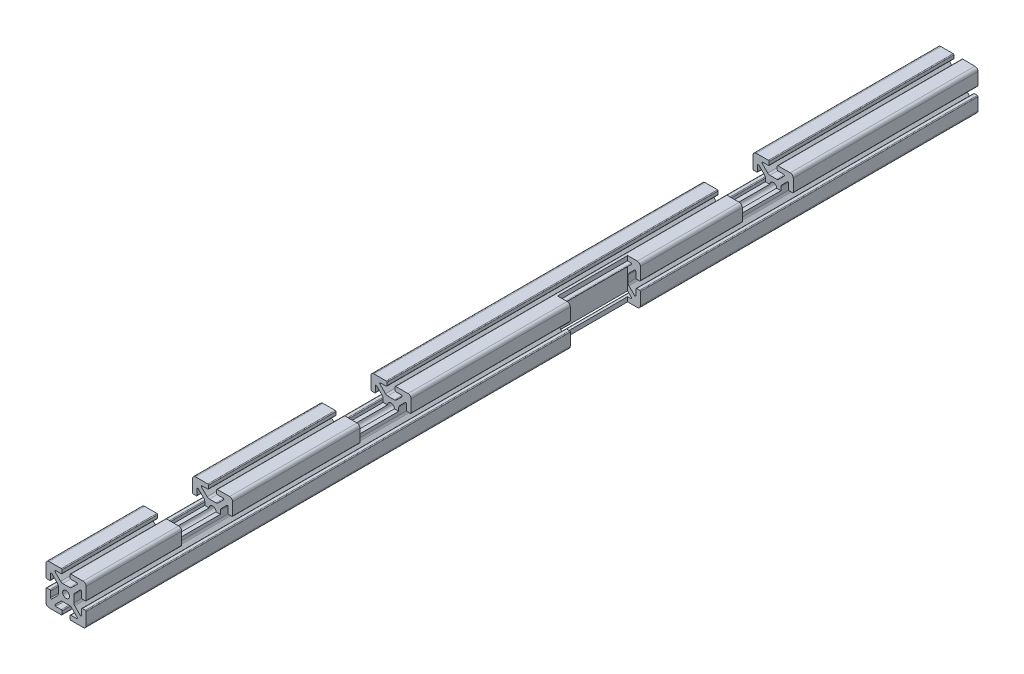
SolidWorks part; units mm, degrees
ref_plane "Front Plane" through (0, 0, 0) normal (0, 0, 1) x (1, 0, 0)
ref_plane "Top Plane" through (0, 0, 0) normal (0, 1, 0) x (1, 0, 0)
ref_plane "Right Plane" through (0, 0, 0) normal (1, 0, 0) x (0, 0, -1)
sketch "Sketch1" plane through (0, 0, 0) normal (0, 0, 1) x (1, 0, 0)
  line L0 (0, 20) -> (0, -20) construction
  line L1 (-20, 0) -> (20, 0) construction
  line L2 (-20, 16.952) -> (-20, 4.7625)
  line L3 (-16.952, 20) -> (-4.7625, 20)
  line L4 (-4.0005, 19.238) -> (-4.0005, 16.2662)
  line L5 (-4.7625, 15.5042) -> (-10.4856, 15.5042)
  line L6 (-11.0244, 14.2034) -> (-5.456, 8.6351)
  line L7 (-14.2034, 11.0244) -> (-8.6351, 5.456)
  line L8 (-15.5042, 10.4856) -> (-15.5042, 4.7625)
  line L9 (-16.2662, 4.0005) -> (-19.238, 4.0005)
  line L10 (0, 0) -> (-20, 20) construction
  line L11 (-3.3367, 7.7572) -> (3.3367, 7.7572)
  line L12 (-7.7572, 3.3367) -> (-7.7572, -3.3367)
  line L13 (16.2662, 4.0005) -> (19.238, 4.0005)
  line L14 (15.5042, 10.4856) -> (15.5042, 4.7625)
  line L15 (20, 16.952) -> (20, 4.7625)
  line L16 (16.952, 20) -> (4.7625, 20)
  line L17 (4.0005, 19.238) -> (4.0005, 16.2662)
  line L18 (4.7625, 15.5042) -> (10.4856, 15.5042)
  line L19 (7.7572, 3.3367) -> (7.7572, -3.3367)
  line L20 (11.0244, 14.2034) -> (5.456, 8.6351)
  line L21 (14.2034, 11.0244) -> (8.6351, 5.456)
  line L22 (-16.2662, -4.0005) -> (-19.238, -4.0005)
  line L23 (-15.5042, -10.4856) -> (-15.5042, -4.7625)
  line L24 (-14.2034, -11.0244) -> (-8.6351, -5.456)
  line L25 (-11.0244, -14.2034) -> (-5.456, -8.6351)
  line L26 (-4.7625, -15.5042) -> (-10.4856, -15.5042)
  line L27 (-4.0005, -19.238) -> (-4.0005, -16.2662)
  line L28 (-16.952, -20) -> (-4.7625, -20)
  line L29 (-20, -16.952) -> (-20, -4.7625)
  line L30 (20, -16.952) -> (20, -4.7625)
  line L31 (16.952, -20) -> (4.7625, -20)
  line L32 (4.0005, -19.238) -> (4.0005, -16.2662)
  line L33 (4.7625, -15.5042) -> (10.4856, -15.5042)
  line L34 (11.0244, -14.2034) -> (5.456, -8.6351)
  line L35 (14.2034, -11.0244) -> (8.6351, -5.456)
  line L36 (15.5042, -10.4856) -> (15.5042, -4.7625)
  line L37 (16.2662, -4.0005) -> (19.238, -4.0005)
  line L38 (-3.3367, -7.7572) -> (3.3367, -7.7572)
  circle A0 centre (0, 0) radius 3.4036
  arc A1 (-20, 16.952) -> (-16.952, 20) centre (-16.952, 16.952) cw
  arc A2 (-14.2034, 11.0244) -> (-15.5042, 10.4856) centre (-14.7422, 10.4856) ccw
  arc A3 (-10.4856, 15.5042) -> (-11.0244, 14.2034) centre (-10.4856, 14.7422) ccw
  arc A4 (-4.7625, 20) -> (-4.0005, 19.238) centre (-4.7625, 19.238) cw
  arc A5 (-20, 4.7625) -> (-19.238, 4.0005) centre (-19.238, 4.7625) ccw
  arc A6 (-15.5042, 4.7625) -> (-16.2662, 4.0005) centre (-16.2662, 4.7625) cw
  arc A7 (-4.0005, 16.2662) -> (-4.7625, 15.5042) centre (-4.7625, 16.2662) cw
  arc A8 (-3.3367, 7.7572) -> (-5.456, 8.6351) centre (-3.3367, 10.7544) cw
  arc A9 (-7.7572, 3.3367) -> (-8.6351, 5.456) centre (-10.7544, 3.3367) ccw
  arc A10 (15.5042, 4.7625) -> (16.2662, 4.0005) centre (16.2662, 4.7625) ccw
  arc A11 (20, 4.7625) -> (19.238, 4.0005) centre (19.238, 4.7625) cw
  arc A12 (20, 16.952) -> (16.952, 20) centre (16.952, 16.952) ccw
  arc A13 (4.7625, 20) -> (4.0005, 19.238) centre (4.7625, 19.238) ccw
  arc A14 (4.0005, 16.2662) -> (4.7625, 15.5042) centre (4.7625, 16.2662) ccw
  arc A15 (3.3367, 7.7572) -> (5.456, 8.6351) centre (3.3367, 10.7544) ccw
  arc A16 (7.7572, 3.3367) -> (8.6351, 5.456) centre (10.7544, 3.3367) cw
  arc A17 (14.2034, 11.0244) -> (15.5042, 10.4856) centre (14.7422, 10.4856) cw
  arc A18 (10.4856, 15.5042) -> (11.0244, 14.2034) centre (10.4856, 14.7422) cw
  arc A19 (-7.7572, -3.3367) -> (-8.6351, -5.456) centre (-10.7544, -3.3367) cw
  arc A20 (-3.3367, -7.7572) -> (-5.456, -8.6351) centre (-3.3367, -10.7544) ccw
  arc A21 (-4.0005, -16.2662) -> (-4.7625, -15.5042) centre (-4.7625, -16.2662) ccw
  arc A22 (-15.5042, -4.7625) -> (-16.2662, -4.0005) centre (-16.2662, -4.7625) ccw
  arc A23 (-20, -4.7625) -> (-19.238, -4.0005) centre (-19.238, -4.7625) cw
  arc A24 (-4.7625, -20) -> (-4.0005, -19.238) centre (-4.7625, -19.238) ccw
  arc A25 (-10.4856, -15.5042) -> (-11.0244, -14.2034) centre (-10.4856, -14.7422) cw
  arc A26 (-14.2034, -11.0244) -> (-15.5042, -10.4856) centre (-14.7422, -10.4856) cw
  arc A27 (-20, -16.952) -> (-16.952, -20) centre (-16.952, -16.952) ccw
  arc A28 (20, -16.952) -> (16.952, -20) centre (16.952, -16.952) cw
  arc A29 (14.2034, -11.0244) -> (15.5042, -10.4856) centre (14.7422, -10.4856) ccw
  arc A30 (10.4856, -15.5042) -> (11.0244, -14.2034) centre (10.4856, -14.7422) ccw
  arc A31 (4.7625, -20) -> (4.0005, -19.238) centre (4.7625, -19.238) cw
  arc A32 (20, -4.7625) -> (19.238, -4.0005) centre (19.238, -4.7625) ccw
  arc A33 (15.5042, -4.7625) -> (16.2662, -4.0005) centre (16.2662, -4.7625) cw
  arc A34 (4.0005, -16.2662) -> (4.7625, -15.5042) centre (4.7625, -16.2662) cw
  arc A35 (3.3367, -7.7572) -> (5.456, -8.6351) centre (3.3367, -10.7544) cw
  arc A36 (7.7572, -3.3367) -> (8.6351, -5.456) centre (10.7544, -3.3367) ccw
  point P29 (-20, 4.0005)
  point P32 (-15.5042, 4.0005)
  point P36 (-4.5782, 7.7572)
  point P68 (0, 7.7572)
  dimension "D4" = 6.8072
  dimension "D5" = 3.048
  dimension "D6" = 0.762
  dimension "D9" = 0.762
  dimension "D10" = 0.762
  dimension "D11" = 4.4958
  dimension "D13" = 2.9972
  dimension "D1" = 40
  dimension "D2" = 40
  dimension "D3" = 12.2428
  dimension "D7" = 8.001
  dimension "D8" = 4.4958
extrude "Extrude1" add sketch "Sketch1" along normal mid plane 889
ref_plane "Plane1" through (0, 0, 0) normal (0, -1, 0) x (-1, 0, 0)
sketch "Sketch3" plane through (0, 0, 0) normal (0, -1, 0) x (-1, 0, 0)
  line L0 (3.4036, 444.5) -> (-3.4036, 444.5) construction
  line L1 (62.2386, 209.55) -> (-47.4218, 209.55)
  line L2 (62.2386, 209.55) -> (62.2386, 260.35)
  line L3 (62.2386, 260.35) -> (-47.4218, 260.35)
  line L4 (-47.4218, 209.55) -> (-47.4218, 260.35)
  line L6 (62.2386, -171.45) -> (-47.4218, -171.45)
  line L7 (62.2386, -171.45) -> (62.2386, -120.65)
  line L8 (62.2386, -120.65) -> (-47.4218, -120.65)
  line L9 (-47.4218, -171.45) -> (-47.4218, -120.65)
  line L10 (62.2386, -298.45) -> (-47.4218, -298.45)
  line L11 (62.2386, -298.45) -> (62.2386, -349.25)
  line L12 (62.2386, -349.25) -> (-47.4218, -349.25)
  line L13 (-47.4218, -298.45) -> (-47.4218, -349.25)
  dimension "D1" = 50.8
  dimension "D2" = 184.15
  dimension "D3" = 50.8
  dimension "D4" = 565.15
  dimension "D5" = 50.8
  dimension "D6" = 742.95
extrude "Cut-Extrude2" cut sketch "Sketch3" against normal up to surface (20 mm away) up to face at (-10.8573, 20, 0)
ref_plane "Plane2" through (20, 0, 0) normal (1, 0, 0) x (0, 0, -1)
sketch "Sketch4" plane through (20, 0, 0) normal (1, 0, 0) x (0, 0, -1)
  line L0 (444.5, -4.7625) -> (444.5, -16.952) construction
  line L1 (38.1, 37.3542) -> (107.95, 37.3542)
  line L2 (38.1, 37.3542) -> (38.1, -37.3542)
  line L3 (38.1, -37.3542) -> (107.95, -37.3542)
  line L4 (107.95, 37.3542) -> (107.95, -37.3542)
  line L5 (38.1, 37.3542) -> (107.95, -37.3542) construction
  line L6 (38.1, -37.3542) -> (107.95, 37.3542) construction
  point P0 (73.025, 0)
  dimension "D1" = 336.55
  dimension "D2" = 406.4
extrude "Cut-Extrude3" cut sketch "Sketch4" against normal blind 12.7
equation "\"D2@Sketch1\" = \"D1@Sketch1\""
